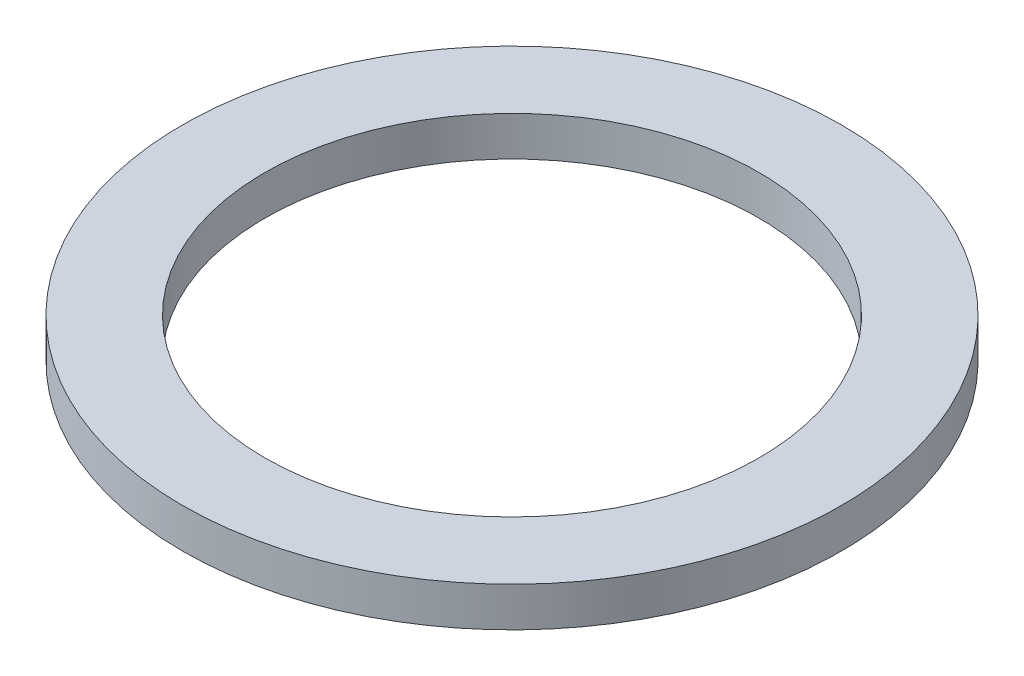
SolidWorks part; units mm, degrees
ref_plane "Front Plane" through (0, 0, 0) normal (0, 0, 1) x (1, 0, 0)
ref_plane "Top Plane" through (0, 0, 0) normal (0, 1, 0) x (1, 0, 0)
ref_plane "Right Plane" through (0, 0, 0) normal (1, 0, 0) x (0, 0, -1)
sketch "Sketch1" plane through (0, 0, 0) normal (0, 1, 0) x (1, 0, 0)
  circle A0 centre (0, 0) radius 7.5
  circle A1 centre (0, 0) radius 10
  dimension "D1" = 20
  dimension "D2" = 15
extrude "Boss-Extrude1" add sketch "Sketch1" along normal blind 1.2
